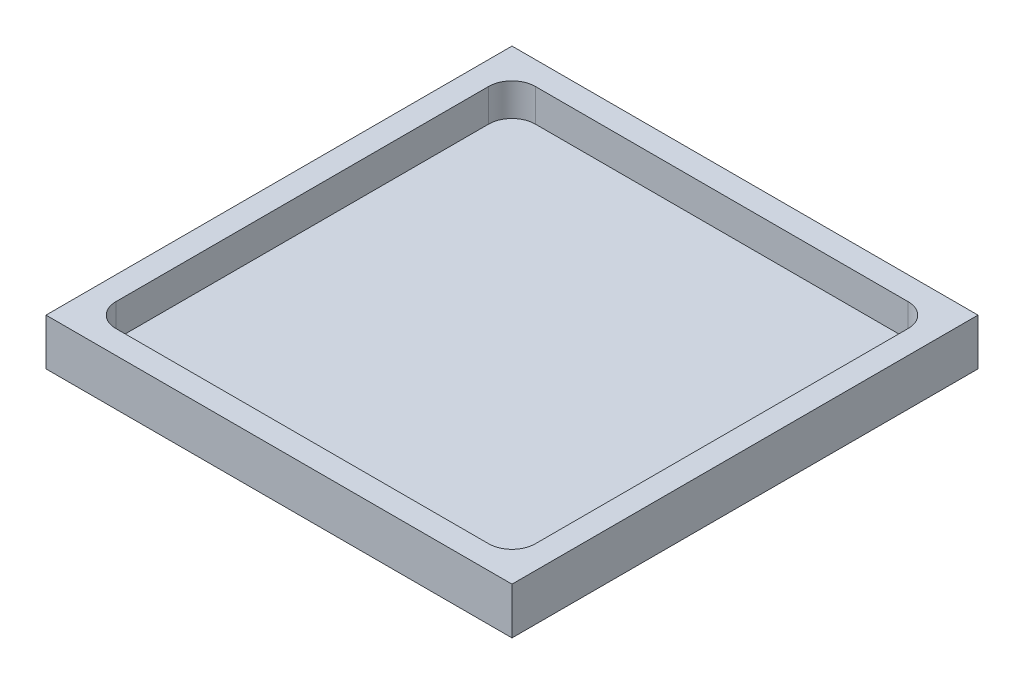
SolidWorks part; units mm, degrees
ref_plane "Front Plane" through (0, 0, 0) normal (0, 0, 1) x (1, 0, 0)
ref_plane "Top Plane" through (0, 0, 0) normal (0, 1, 0) x (1, 0, 0)
ref_plane "Right Plane" through (0, 0, 0) normal (1, 0, 0) x (0, 0, -1)
sketch "Sketch2" plane through (0, 0, 0) normal (0, 1, 0) x (1, 0, 0)
  line L1 (0, 0) -> (100, 0)
  line L2 (0, 0) -> (0, 100)
  line L3 (0, 100) -> (100, 100)
  line L4 (100, 0) -> (100, 100)
  dimension "D1" = 100
  dimension "D2" = 100
extrude "Boss-Extrude1" add sketch "Sketch2" along normal blind 10
sketch "Sketch3" plane through (0, 10, 0) normal (0, 1, 0) x (1, 0, 0)
  line L0 (100, 100) -> (0, 100) construction
  line L1 (5, 95) -> (95, 95)
  line L2 (5, 95) -> (5, 5)
  line L3 (5, 5) -> (95, 5)
  line L4 (95, 95) -> (95, 5)
  line L5 (0, 100) -> (0, 0) construction
  line L6 (50, 100) -> (50, 0) construction
  line L7 (0, 0) -> (100, 0) construction
  line L8 (0, 50) -> (100, 50) construction
  line L9 (100, 0) -> (100, 100) construction
  point P12 (50, 95)
  point P13 (50, 95)
  point P14 (50, 95)
  point P15 (5, 50)
  point P20 (0, 0)
  dimension "D1" = 5
  dimension "D2" = 5
extrude "Cut-Extrude1" cut sketch "Sketch3" against normal blind 7
fillet "Fillet1" [suppressed] radius 5
fillet "Fillet2" radius 5 4 edges at (95, 6.5, -95) (95, 6.5, -5) (5, 6.5, -5) (5, 6.5, -95)
